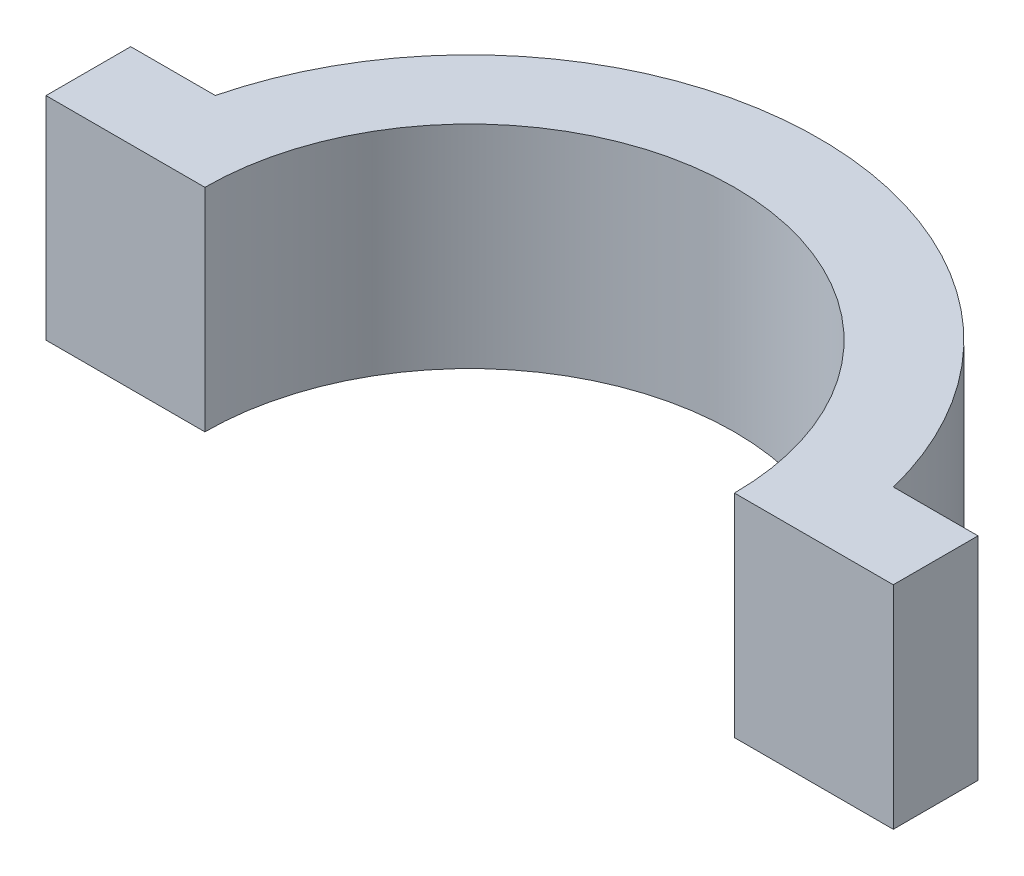
SolidWorks part; units mm, degrees
ref_plane "Front Plane" through (0, 0, 0) normal (0, 0, 1) x (1, 0, 0)
ref_plane "Top Plane" through (0, 0, 0) normal (0, 1, 0) x (1, 0, 0)
ref_plane "Right Plane" through (0, 0, 0) normal (1, 0, 0) x (0, 0, -1)
sketch "Sketch1" plane through (0, 0, 0) normal (0, 1, 0) x (1, 0, 0)
  line L0 (0, 4) -> (3.9922, 4)
  line L1 (0, 0) -> (40, 0)
  line L2 (0, 0) -> (0, 4)
  line L4 (40, 0) -> (40, 4)
  line L5 (40, 4) -> (36.0078, 4)
  circle A0 centre (20, 0) radius 12.5
  arc A1 (3.5, 0) -> (36.5, 0) centre (20, 0) ccw
  arc A2 (36.0078, 4) -> (3.9922, 4) centre (20, 0) ccw
  dimension "D2" = 40
  dimension "D3" = 25
  dimension "D5" = 33
  dimension "D1" = 4
  dimension "D4" = 4
extrude "Boss-Extrude1" add sketch "Sketch1" along normal blind 10 contours L5 A2 L0 L2 L1 A0 L4
